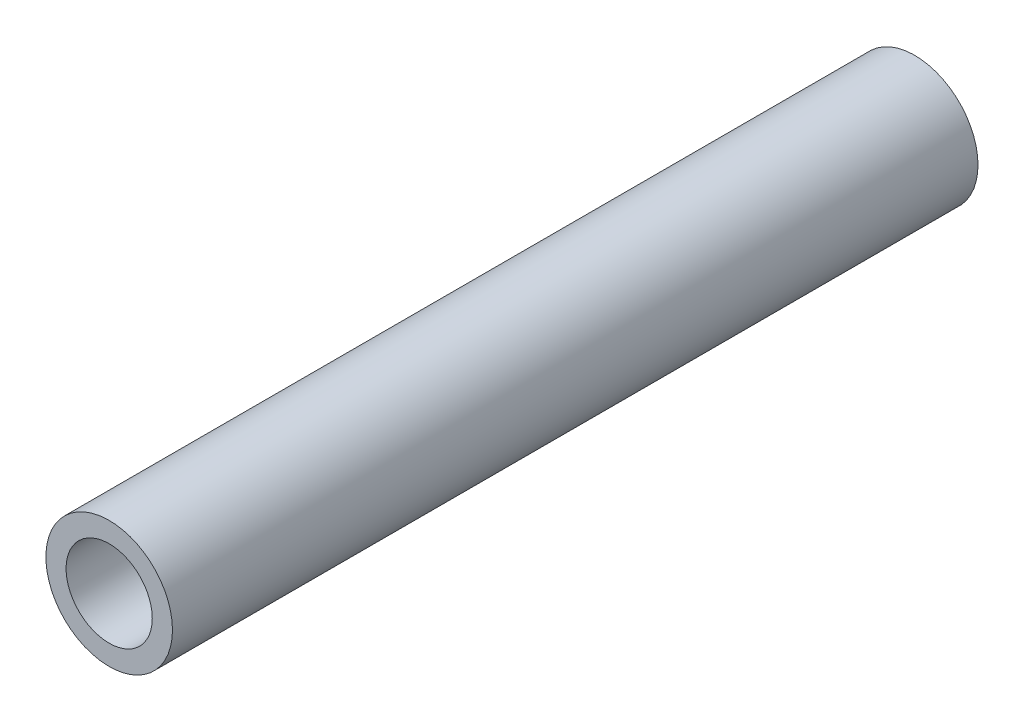
SolidWorks part; units mm, degrees
ref_plane "Front Plane" through (0, 0, 0) normal (0, 0, 1) x (1, 0, 0)
ref_plane "Top Plane" through (0, 0, 0) normal (0, 1, 0) x (1, 0, 0)
ref_plane "Right Plane" through (0, 0, 0) normal (1, 0, 0) x (0, 0, -1)
sketch "Sketch1" plane through (0, 0, 0) normal (0, 0, 1) x (1, 0, 0)
  line L0 (164.15, 2198.81) -> (164.15, 2138.81) construction
  circle A0 centre (164.15, 2168.81) radius 11
  circle A2 centre (164.15, 2168.81) radius 7.49
  point P0 (164.15, 2168.81)
  dimension "D1" = 22
  dimension "D2" = 14.98
extrude "Boss-Extrude1" add sketch "Sketch1" along normal blind 100 and the other way blind 40
